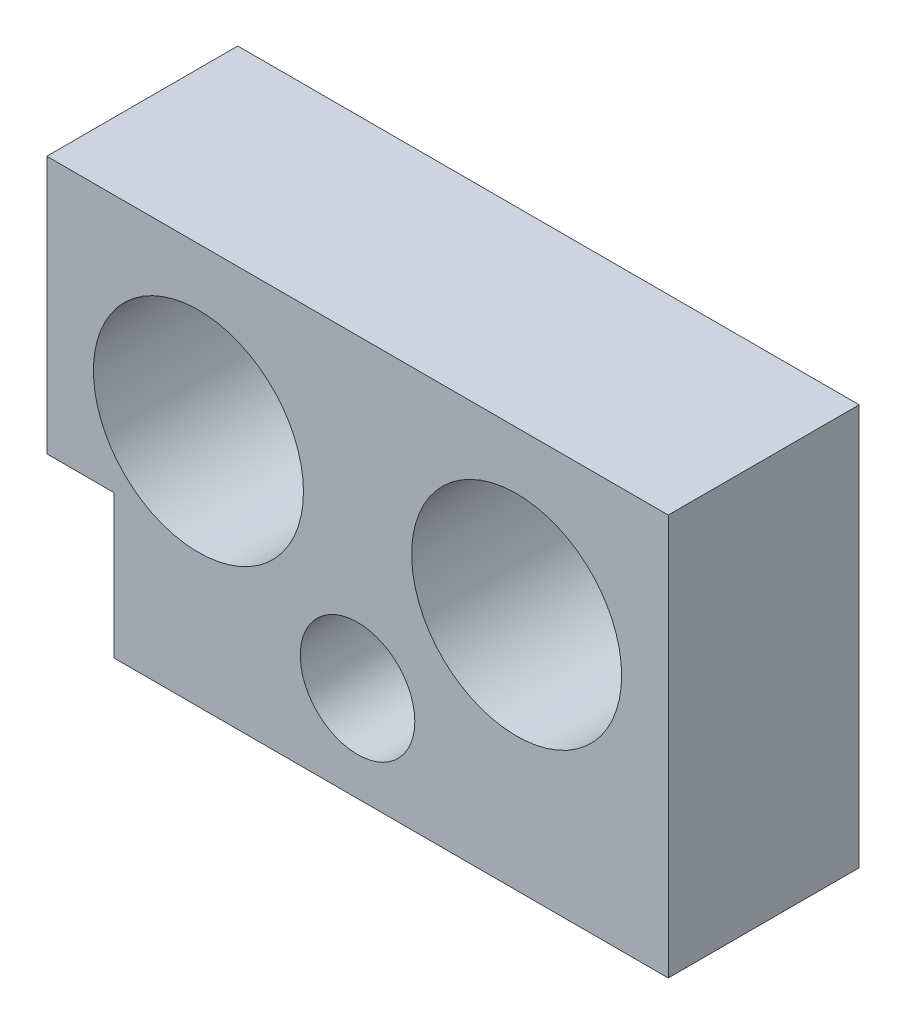
SolidWorks part; units mm, degrees
material "Manual Density from Real Component Plastica Fusoliera"
ref_plane "Piano frontale" through (0, 0, 0) normal (0, 0, 1) x (1, 0, 0)
ref_plane "Piano superiore" through (0, 0, 0) normal (0, 1, 0) x (1, 0, 0)
ref_plane "Piano destro" through (0, 0, 0) normal (1, 0, 0) x (0, 0, -1)
sketch "Schizzo1" plane through (0, 0, 0) normal (0, 0, 1) x (1, 0, 0)
  line L0 (-15.55, 0) -> (15.55, 0) construction
  line L2 (-30.55, 15) -> (30.55, 15) construction
  line L3 (-30.55, 15) -> (-30.55, -25) construction
  line L4 (-30.55, -25) -> (30.55, -25)
  line L5 (30.55, 15) -> (30.55, -25) construction
  line L6 (-30.55, -15) -> (30.55, -15) construction
  line L7 (-30.55, -25) -> (-32.55, -25)
  line L8 (-32.55, -25) -> (-32.55, 17)
  line L10 (32.55, 17) -> (32.55, -25)
  line L11 (32.55, -25) -> (30.55, -25)
  line L12 (-32.55, 17) -> (32.55, 17)
  circle A0 centre (-15.55, 0) radius 15 construction
  circle A1 centre (15.55, 0) radius 15 construction
  point P5 (0, 0)
  dimension "D2" = 30
  dimension "D1" = 31.1
  dimension "D3" = 10
  dimension "D4" = 2
  dimension "D5" = 2
  dimension "D6" = 2
extrude "ParallelepipedoBlocco" add sketch "Schizzo1" along normal blind 20
sketch "Schizzo2" plane through (0, 0, 20) normal (0, 0, 1) x (1, 0, 0)
  line L0 (-16.665, 0) -> (16.665, 0) construction
  line L1 (32.55, 17) -> (-32.55, 17) construction
  line L3 (-32.55, 15) -> (32.55, 15) construction
  line L4 (-32.55, 17) -> (-32.55, -25) construction
  line L5 (32.55, -25) -> (32.55, 17) construction
  circle A0 centre (-16.665, 0) radius 11
  circle A1 centre (16.665, 0) radius 11
  circle A2 centre (0, -15) radius 6
  point P4 (0, 0)
  dimension "D1" = 22
  dimension "D3" = 12
  dimension "D2" = 2
  dimension "D4" = 33.33
  dimension "D5" = 15
extrude "ForiTubiMotori" cut sketch "Schizzo2" against normal through all
ref_plane "PianoMedio" through (0, 0, 10) normal (0, 0, 1) x (1, 0, 0)
sketch "Schizzo3" plane through (0, 0, 20) normal (0, 0, 1) x (1, 0, 0)
  line L1 (-32.55, -25) -> (-25.5, -25)
  line L2 (-32.55, -25) -> (-32.55, -10)
  line L3 (-32.55, -10) -> (-25.5, -10)
  line L4 (-25.5, -25) -> (-25.5, -10)
  dimension "D1" = 7.05
  dimension "D2" = 15
extrude "SpazioMovimentoLevetta" cut sketch "Schizzo3" against normal through all
